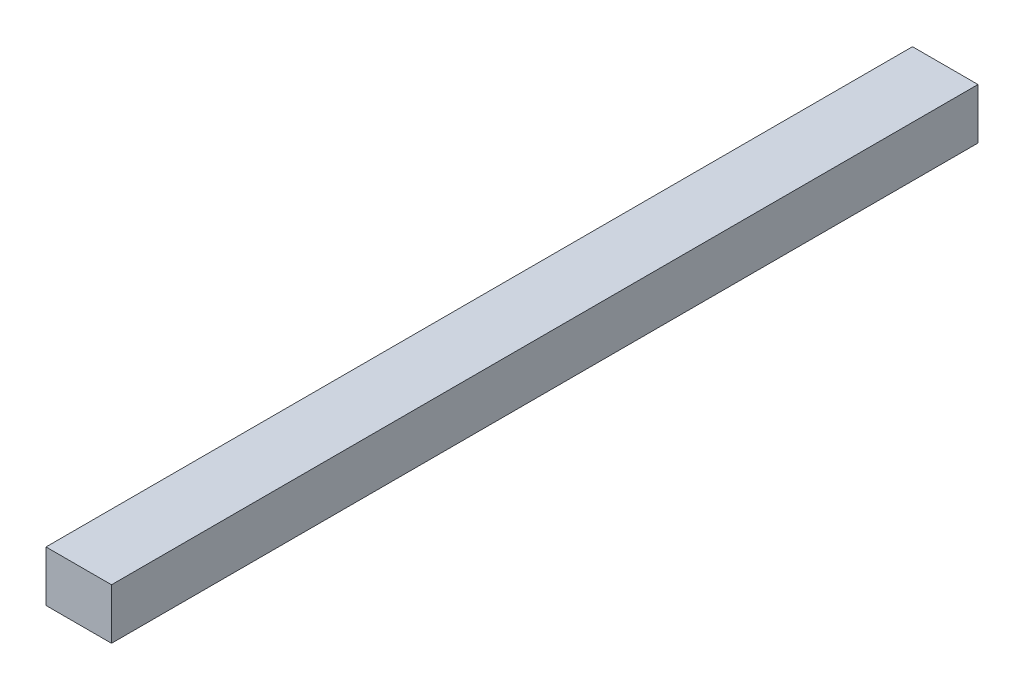
SolidWorks part; units mm, degrees
ref_plane "Front Plane" through (0, 0, 0) normal (0, 0, 1) x (1, 0, 0)
ref_plane "Top Plane" through (0, 0, 0) normal (0, 1, 0) x (1, 0, 0)
ref_plane "Right Plane" through (0, 0, 0) normal (1, 0, 0) x (0, 0, -1)
sketch "Sketch1" plane through (0, 0, 0) normal (0, 0, 1) x (1, 0, 0)
  line L1 (-1.55, -1.2) -> (1.55, -1.2)
  line L2 (-1.55, -1.2) -> (-1.55, 1.2)
  line L3 (-1.55, 1.2) -> (1.55, 1.2)
  line L4 (1.55, -1.2) -> (1.55, 1.2)
  line L5 (-1.55, -1.2) -> (1.55, 1.2) construction
  line L6 (-1.55, 1.2) -> (1.55, -1.2) construction
  point P0 (0, 0)
  dimension "D1" = 3.1
  dimension "D2" = 2.4
extrude "Boss-Extrude1" add sketch "Sketch1" along normal blind 41
